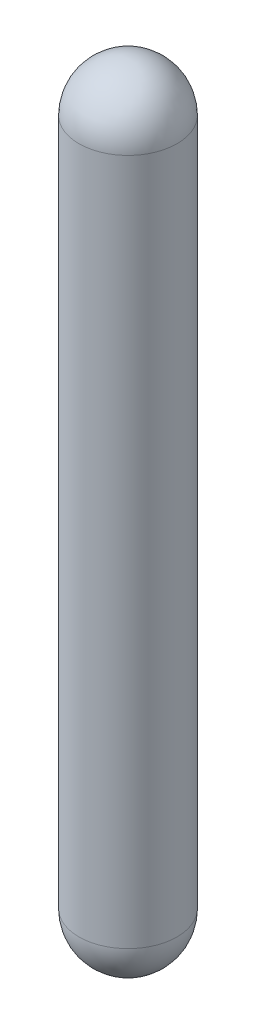
SolidWorks part; units mm, degrees
ref_plane "Front Plane" through (0, 0, 0) normal (0, 0, 1) x (1, 0, 0)
ref_plane "Top Plane" through (0, 0, 0) normal (0, 1, 0) x (1, 0, 0)
ref_plane "Right Plane" through (0, 0, 0) normal (1, 0, 0) x (0, 0, -1)
sketch "Sketch1" plane through (0, 0, 0) normal (0, 1, 0) x (1, 0, 0)
  circle A0 centre (0, 0) radius 3.175
  dimension "D1" = 6.35
extrude "Boss-Extrude1" add sketch "Sketch1" along normal mid plane 50.8
fillet "Fillet1" radius 3.175 2 edges at (0, -25.4, 3.175) (0, 25.4, 3.175)
